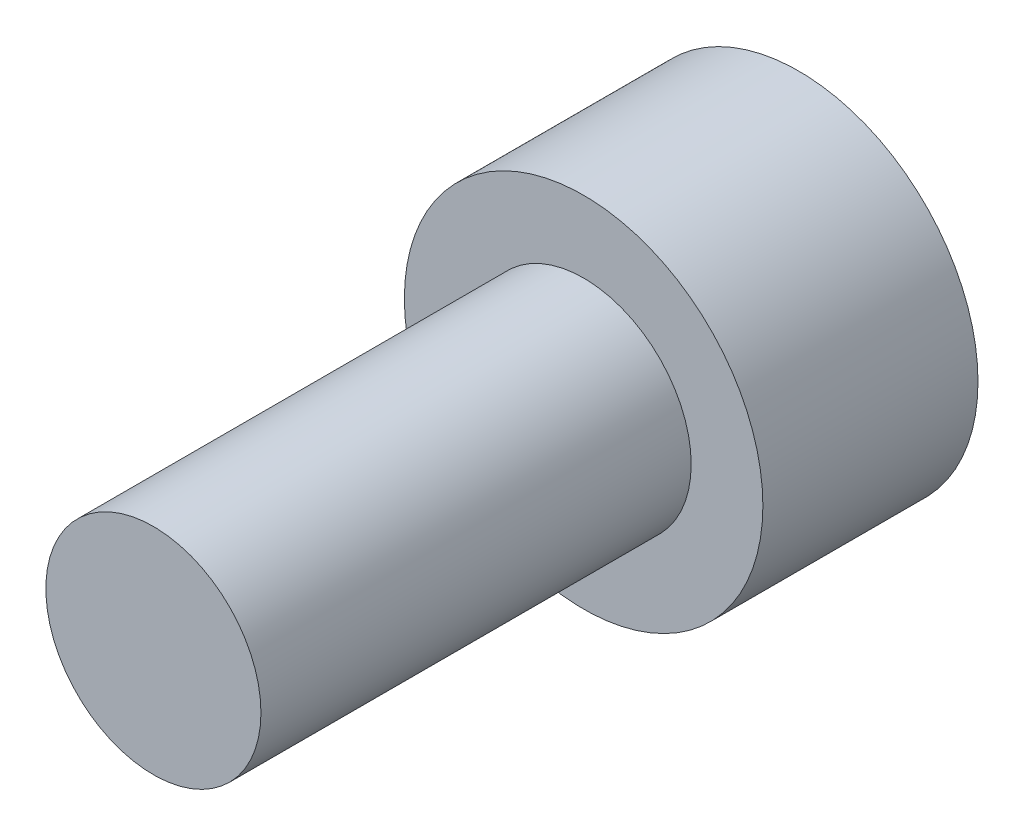
SolidWorks part; units mm, degrees
material "Acero aleado"
ref_plane "Alzado" through (0, 0, 0) normal (0, 0, 1) x (1, 0, 0)
ref_plane "Planta" through (0, 0, 0) normal (0, 1, 0) x (1, 0, 0)
ref_plane "Vista lateral" through (0, 0, 0) normal (1, 0, 0) x (0, 0, -1)
sketch "Croquis1" plane through (0, 0, 0) normal (0, 0, 1) x (1, 0, 0)
  circle A0 centre (0, 0) radius 5
  dimension "D1" = 10
extrude "Cabeza" add sketch "Croquis1" along normal blind 6 from offset 6
sketch "Croquis2" plane through (0, 0, 0) normal (0, 0, 1) x (1, 0, 0)
  circle A0 centre (0, 0) radius 3
  dimension "D1" = 6
extrude "Cuerpo" add sketch "Croquis2" along normal blind 12
sketch "Croquis3" plane through (0, 0, 0) normal (0, 0, 1) x (1, 0, 0)
  line L0 (2.8868, 0) -> (1.4434, 2.5)
  line L1 (1.4434, 2.5) -> (-1.4434, 2.5)
  line L2 (-1.4434, 2.5) -> (-2.8868, 0)
  line L3 (-2.8868, 0) -> (-1.4434, -2.5)
  line L4 (-1.4434, -2.5) -> (1.4434, -2.5)
  line L5 (1.4434, -2.5) -> (2.8868, 0)
  dimension "D1" = 2.8868
  dimension "D2" = 1.4434
  dimension "D3" = 2.5
  dimension "D4" = 1.4434
  dimension "D5" = 2.5
  dimension "D6" = 2.8868
  dimension "D7" = 1.4434
  dimension "D8" = 2.5
  dimension "D9" = 1.4434
  dimension "D10" = 2.5
extrude "Hexagono_interior" cut sketch "Croquis3" along normal blind 3 from offset 6
